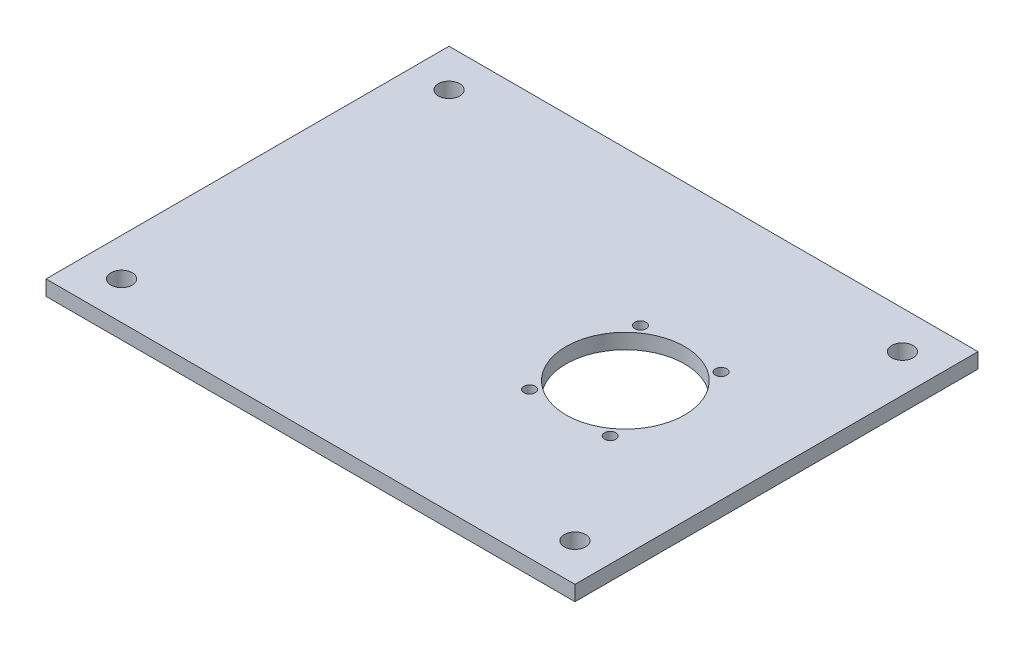
SolidWorks part; units mm, degrees
ref_plane "Front Plane" through (0, 0, 0) normal (0, 0, 1) x (1, 0, 0)
ref_plane "Top Plane" through (0, 0, 0) normal (0, 1, 0) x (1, 0, 0)
ref_plane "Right Plane" through (0, 0, 0) normal (1, 0, 0) x (0, 0, -1)
sketch "Sketch1" plane through (0, 0, 0) normal (0, 1, 0) x (1, 0, 0)
  line L1 (-105, -80) -> (105, -80)
  line L2 (-105, -80) -> (-105, 80)
  line L3 (-105, 80) -> (105, 80)
  line L4 (105, -80) -> (105, 80)
  circle A0 centre (45, 0) radius 23.55
  circle A1 centre (-90, -65) radius 4.25
  circle A2 centre (90, -65) radius 4.25
  circle A3 centre (-90, 65) radius 4.25
  circle A4 centre (90, 65) radius 4.25
  circle A5 centre (29, -22) radius 2.25
  circle A6 centre (61, -22) radius 2.25
  circle A7 centre (29, 22) radius 2.25
  circle A8 centre (61, 22) radius 2.25
extrude "Plate_Extrude" add sketch "Sketch1" along normal blind 6
equation "\"ValveDiameter\" = 50mm"
equation "\"MotorGearTeeth\" = 40"
equation "\"OutputGearTeeth\" = 80"
equation "\"GearModule\" = 1.5mm"
equation "\"PressureAngle\" = 20deg"
equation "\"GearCenterDistance\" = 90mm"
equation "\"GearWidth\" = 18mm"
equation "\"OutputShaftDiameter\" = 20mm"
equation "\"BearingOD\" = 47mm"
equation "\"BearingWidth\" = 14mm"
equation "\"PlateThickness\" = 6mm"
equation "\"ValveRotation\" = 90deg"
